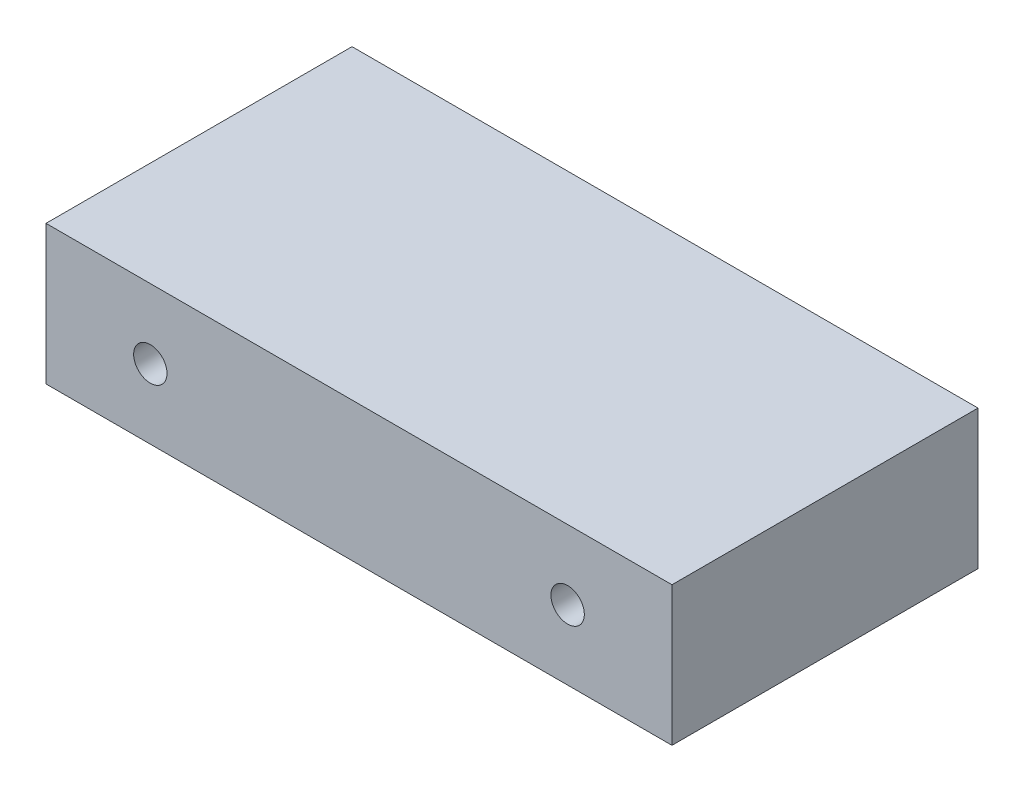
SolidWorks part; units mm, degrees
material "ABS"
ref_plane "Plan de face" through (0, 0, 0) normal (0, 0, 1) x (1, 0, 0)
ref_plane "Plan de dessus" through (0, 0, 0) normal (0, 1, 0) x (1, 0, 0)
ref_plane "Plan de droite" through (0, 0, 0) normal (1, 0, 0) x (0, 0, -1)
sketch "Esquisse1" plane through (0, 0, 0) normal (0, 1, 0) x (1, 0, 0)
  line L1 (-22.5, -22) -> (22.5, -22)
  line L2 (-22.5, -22) -> (-22.5, 0)
  line L3 (-22.5, 0) -> (22.5, 0)
  line L4 (22.5, -22) -> (22.5, 0)
  dimension "D1" = 22
  dimension "D2" = 45
extrude "Boss.-Extru.1" add sketch "Esquisse1" along normal mid plane 10
sketch "Esquisse2" plane through (0, 0, 22) normal (0, 0, 1) x (1, 0, 0)
  line L0 (-15, 0) -> (15, 0) construction
  circle A0 centre (-15, 0) radius 1.2
  circle A1 centre (15, 0) radius 1.2
  dimension "D1" = 30
  dimension "D2" = 2.4
extrude "Enlèv. mat.-Extru.1" cut sketch "Esquisse2" against normal through all
